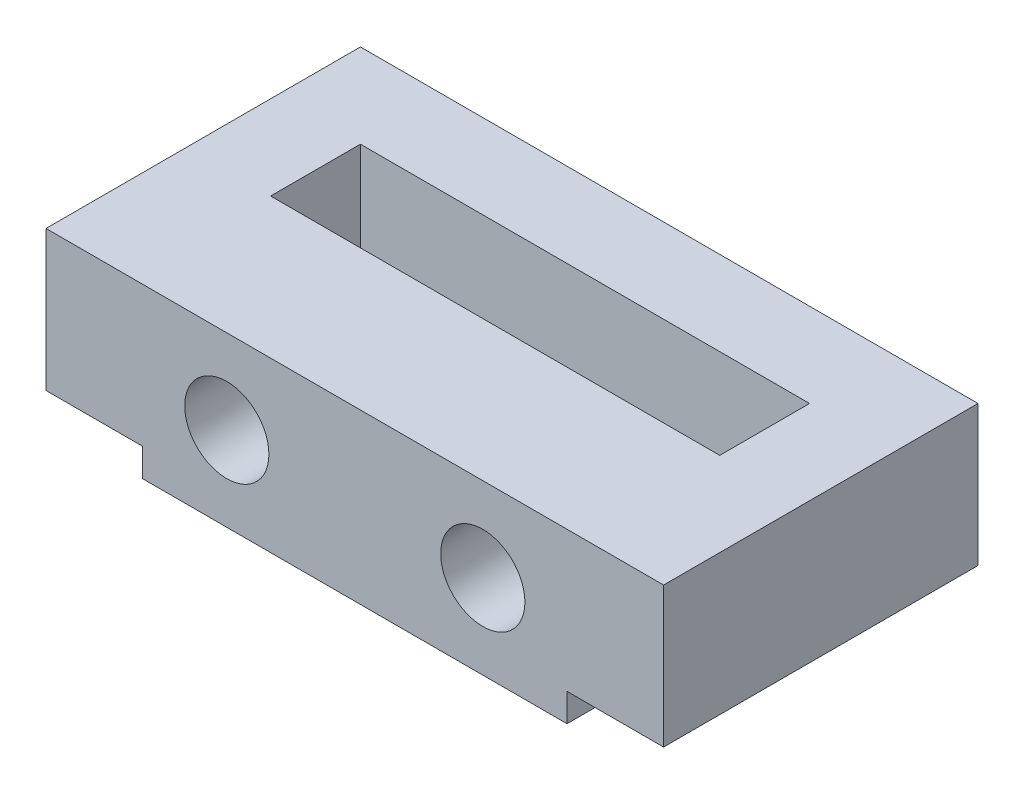
SolidWorks part; units mm, degrees
ref_plane "Front" through (0, 0, 0) normal (0, 0, 1) x (1, 0, 0)
ref_plane "Top" through (0, 0, 0) normal (0, 1, 0) x (1, 0, 0)
ref_plane "Right" through (0, 0, 0) normal (1, 0, 0) x (0, 0, -1)
sketch "Эскиз1" plane through (0, 0, 0) normal (0, 0, 1) x (1, 0, 0)
  line L0 (0, 0) -> (9.12, 0) construction
  line L1 (-3, 3) -> (12.12, 3)
  line L2 (-3, 3) -> (-3, -3)
  line L3 (-3, -3) -> (12.12, -3)
  line L4 (12.12, 3) -> (12.12, -3)
  line L5 (4.56, 0) -> (4.56, 3) construction
  circle A0 centre (0, 0) radius 1.5
  circle A1 centre (9.12, 0) radius 1.5
  point P13 (-1.4979, 0.0787)
  dimension "D1" = 3
  dimension "D2" = 9.12
  dimension "D3" = 3
  dimension "D4" = 3
extrude "Бобышка-Вытянуть1" add sketch "Эскиз1" along normal blind 5
sketch "Эскиз2" plane through (0, 3, 0) normal (0, 1, 0) x (1, 0, 0)
  line L0 (12.12, -5) -> (15.56, -5)
  line L1 (12.12, -5) -> (12.12, 0)
  line L2 (15.56, -5) -> (15.56, 6.2)
  line L3 (15.56, 6.2) -> (-6.44, 6.2)
  line L4 (-6.44, 6.2) -> (-6.44, -5)
  line L5 (-6.44, -5) -> (-3, -5)
  line L6 (12.12, 0) -> (12.56, 0)
  line L7 (12.56, 0) -> (12.56, 3.2)
  line L8 (12.56, 3.2) -> (-3.44, 3.2)
  line L9 (-3.44, 3.2) -> (-3.44, 0)
  line L10 (-3.44, 0) -> (-3, 0)
  line L11 (4.56, -5) -> (4.56, 0) construction
  line L12 (12.12, -5) -> (-3, -5) construction
  line L13 (12.12, 0) -> (-3, 0) construction
  line L14 (-3, -5) -> (-3, 0)
  dimension "D1" = 16
  dimension "D2" = 3
  dimension "D3" = 3
  dimension "D4" = 3.2
extrude "Бобышка-Вытянуть2" add sketch "Эскиз2" against normal blind 5
